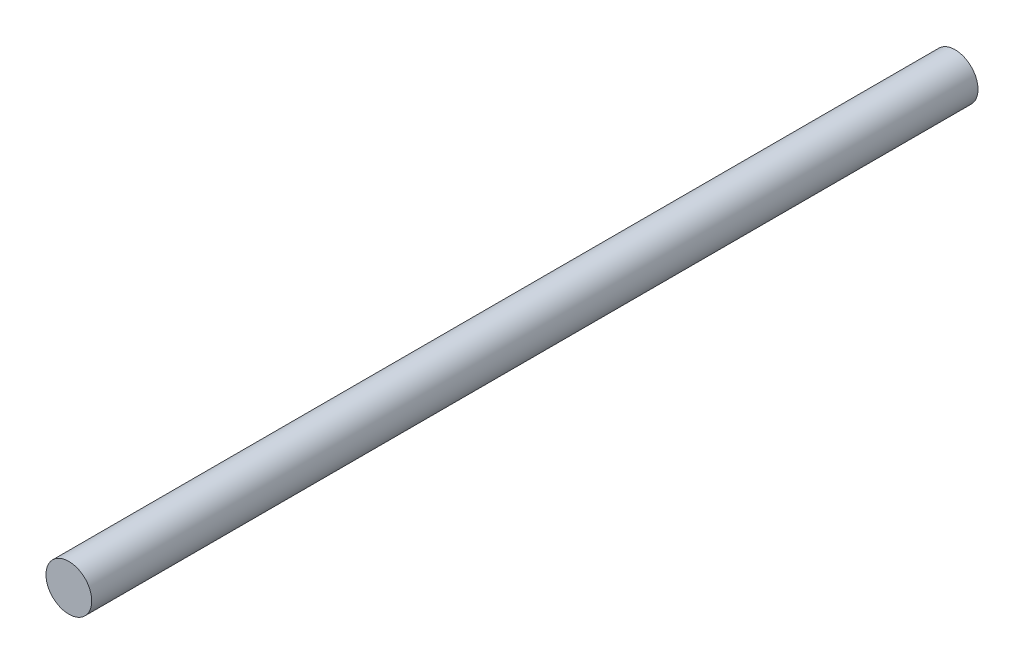
SolidWorks part; units mm, degrees
ref_plane "Alzado" through (0, 0, 0) normal (0, 0, 1) x (1, 0, 0)
ref_plane "Planta" through (0, 0, 0) normal (0, 1, 0) x (1, 0, 0)
ref_plane "Vista lateral" through (0, 0, 0) normal (1, 0, 0) x (0, 0, -1)
sketch "Croquis1" plane through (0, 0, 0) normal (0, 0, 1) x (1, 0, 0)
  circle A0 centre (-61.2815, 29.6958) radius 31
  point P2 (-155.8492, 48.8133)
extrude "Saliente-Extruir1" add sketch "Croquis1" along normal blind 1200
